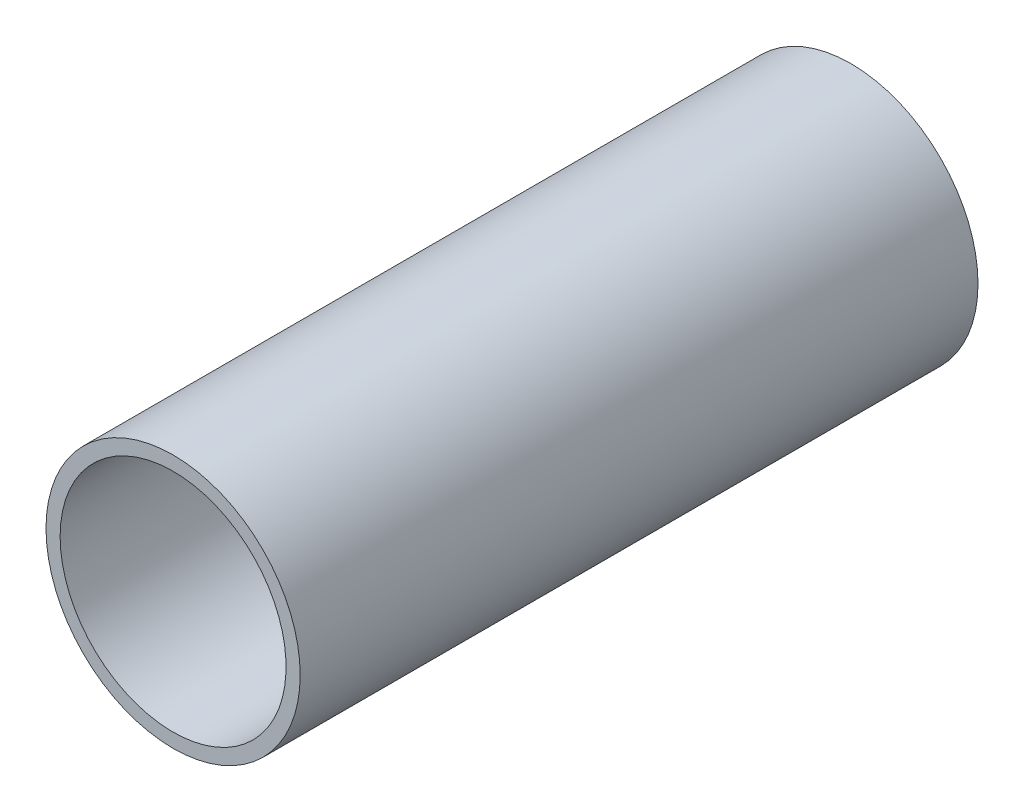
SolidWorks part; units mm, degrees
material "PVC Rigid"
ref_plane "Front Plane" through (0, 0, 0) normal (0, 0, 1) x (1, 0, 0)
ref_plane "Top Plane" through (0, 0, 0) normal (0, 1, 0) x (1, 0, 0)
ref_plane "Right Plane" through (0, 0, 0) normal (1, 0, 0) x (0, 0, -1)
sketch "Sketch1" plane through (0, 0, 0) normal (0, 0, 1) x (1, 0, 0)
  circle A0 centre (0, 0) radius 57.15
  circle A1 centre (0, 0) radius 50.8
  dimension "D1" = 114.3
  dimension "D2" = 101.6
extrude "Boss-Extrude1" add sketch "Sketch1" along normal blind 304.8
